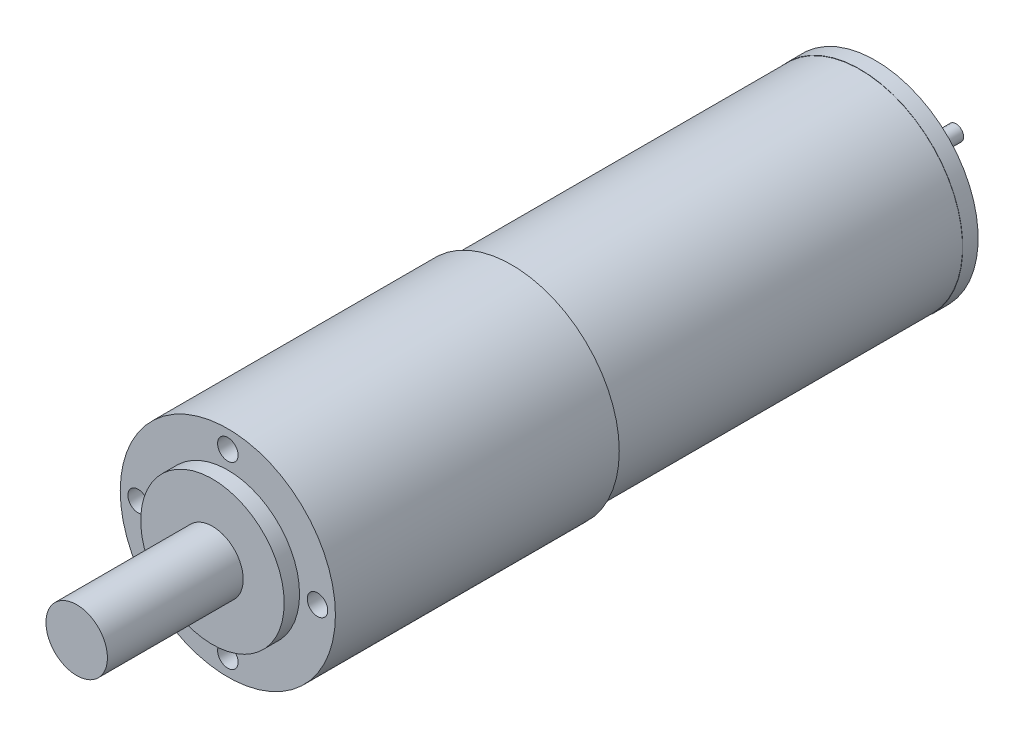
SolidWorks part; units mm, degrees
ref_plane "Plan de face" through (0, 0, 0) normal (0, 0, 1) x (1, 0, 0)
ref_plane "Plan de dessus" through (0, 0, 0) normal (0, 1, 0) x (1, 0, 0)
ref_plane "Plan de droite" through (0, 0, 0) normal (1, 0, 0) x (0, 0, -1)
sketch "Esquisse1" plane through (0, 0, 0) normal (0, 0, 1) x (1, 0, 0)
  circle A0 centre (0, 0) radius 20
  dimension "D1" = 40
extrude "Boss.-Extru.1" add sketch "Esquisse1" along normal blind 71
sketch "Esquisse2" plane through (0, 0, 0) normal (0, 0, -1) x (-1, 0, 0)
  circle A0 centre (0, 0) radius 4
  dimension "D1" = 8
extrude "Boss.-Extru.2" add sketch "Esquisse2" along normal blind 1.35
sketch "Esquisse3" plane through (0, 0, 0) normal (0, 0, -1) x (-1, 0, 0)
  circle A0 centre (0, 0) radius 1.5
  dimension "D1" = 3
extrude "Boss.-Extru.3" add sketch "Esquisse3" along normal blind 15.7
sketch "Esquisse4" plane through (0, 0, 71) normal (0, 0, 1) x (1, 0, 0)
  circle A0 centre (0, 0) radius 21
  dimension "D1" = 42
sketch "Esquisse11" plane through (0, 0, 0) normal (0, 0, -1) x (-1, 0, 0)
  circle A0 centre (0, 0) radius 20.05
  circle A1 centre (0, 0) radius 20 construction
  dimension "D1" = 0.05
extrude "Boss.-Extru.8" add sketch "Esquisse11" against normal blind 3
sketch "Esquisse12" plane through (0, 0, 0) normal (0, 0, -1) x (-1, 0, 0)
  line L0 (0, -27.4817) -> (0, 30.8277) construction
  line L1 (33.5191, 0) -> (-33.7773, 0) construction
  line L2 (34.4503, -5.1486) -> (-38.132, 5.6989) construction
  line L3 (13.5537, -1.0435) -> (19.3492, -2.5964)
  line L4 (-13.5847, -0.4975) -> (-19.5188, 0.3893)
  line L5 (-13.5847, -0.4975) -> (-12.8456, 4.4476)
  line L6 (-12.8456, 4.4476) -> (-18.7797, 5.3344)
  line L7 (-19.5188, 0.3893) -> (-18.7797, 5.3344)
  line L8 (13.5537, -1.0435) -> (12.2596, -5.8731)
  line L9 (12.2596, -5.8731) -> (18.0551, -7.426)
  line L10 (19.3492, -2.5964) -> (18.0551, -7.426)
  line L11 (21.1546, 15.6536) -> (-29.1339, -21.5579) construction
  line L12 (3.1711, -27.8328) -> (-4.4118, 38.7223) construction
  circle A0 centre (0, 0) radius 15.2 construction
  circle A1 centre (1.7207, -15.1023) radius 1
  circle A2 centre (-1.7207, 15.1023) radius 1
  circle A3 centre (-12.2186, -9.0413) radius 1
  circle A5 centre (0, 0) radius 12.7 construction
  circle A6 centre (10.209, 7.5542) radius 0.8
  circle A7 centre (-10.209, -7.5542) radius 0.8
  circle A8 centre (-9.0413, 12.2186) radius 1
  circle A9 centre (12.2186, 9.0413) radius 1
  circle A10 centre (9.0413, -12.2186) radius 1
  point P17 (0, 0)
  point P45 (0, 0)
  dimension "D3" = 6
  dimension "D4" = 2.5
  dimension "D8" = 4
  dimension "D1" = 8.5
  dimension "D2" = 5
  dimension "D5" = 2
  dimension "D6" = 45
  dimension "D7" = 60
extrude "Enlèv. mat.-Extru.4" cut sketch "Esquisse12" against normal blind 1
extrude "Boss.-Extru.9" add sketch "Esquisse4" along normal blind 55.4
sketch "Esquisse13" plane through (0, 0, 126.4) normal (0, 0, 1) x (1, 0, 0)
  circle A0 centre (0, 0) radius 14
extrude "Boss.-Extru.10" add sketch "Esquisse13" along normal blind 3
sketch "Esquisse14" plane through (0, 0, 129.4) normal (0, 0, 1) x (1, 0, 0)
  circle A0 centre (0, 0) radius 6
extrude "Boss.-Extru.11" add sketch "Esquisse14" along normal blind 26.5
sketch "Esquisse15" plane through (0, 0, 126.4) normal (0, 0, 1) x (1, 0, 0)
  line L0 (0, 21.3613) -> (0, -50.5757) construction
  line L1 (-29.071, 0) -> (40.2006, 0) construction
  circle A0 centre (0, 0) radius 17.5 construction
  circle A1 centre (0, -17.5) radius 2
  circle A2 centre (-17.5, 0) radius 2
  circle A3 centre (0, 17.5) radius 2
  circle A4 centre (17.5, 0) radius 2
  point P18 (0, 0)
  dimension "D1" = 4
extrude "Enlèv. mat.-Extru.5" cut sketch "Esquisse15" against normal blind 6
